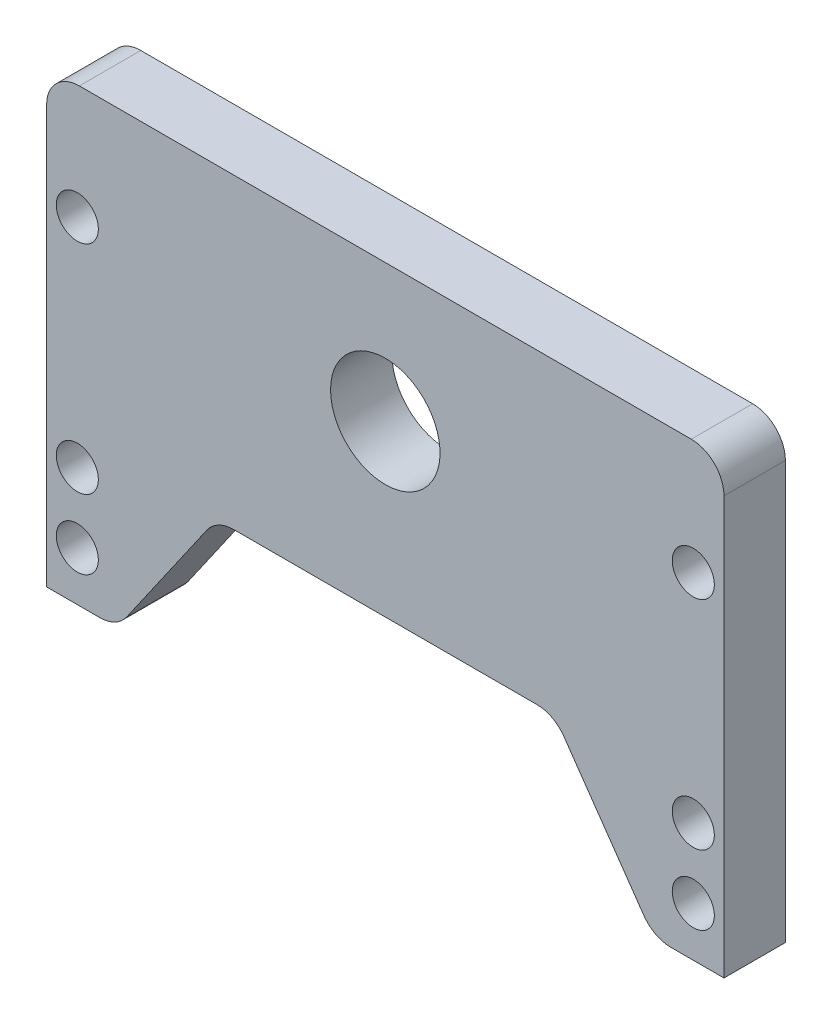
SolidWorks part; units mm, degrees
ref_plane "Front Plane" through (0, 0, 0) normal (0, 0, 1) x (1, 0, 0)
ref_plane "Top Plane" through (0, 0, 0) normal (0, 1, 0) x (1, 0, 0)
ref_plane "Right Plane" through (0, 0, 0) normal (1, 0, 0) x (0, 0, -1)
sketch "Sketch1" plane through (0, 0, 0) normal (0, 0, 1) x (1, 0, 0)
  line L0 (-26.27, -11.1125) -> (-22.1435, -11.1125)
  line L1 (-26.27, -11.1125) -> (-26.27, 21.2725)
  line L2 (-23.7299, 23.8125) -> (23.7299, 23.8125)
  line L3 (26.2699, 21.2725) -> (26.27, -11.1125)
  line L4 (26.27, -11.1125) -> (22.1435, -11.1125)
  line L5 (20.0581, -10.0226) -> (13.8467, -1.0899)
  line L6 (11.7613, 0) -> (-11.7613, 0)
  line L7 (-13.8467, -1.0899) -> (-20.0581, -10.0226)
  line L8 (0, -1000) -> (0, 49000) construction
  line L9 (26.2699, 19.6944) -> (21.5074, 19.6944) construction
  arc A0 (22.1435, -11.1125) -> (20.0581, -10.0226) centre (22.1435, -8.5725) cw
  arc A1 (-22.1435, -11.1125) -> (-20.0581, -10.0226) centre (-22.1435, -8.5725) ccw
  arc A2 (-11.7613, 0) -> (-13.8467, -1.0899) centre (-11.7613, -2.54) ccw
  arc A3 (13.8467, -1.0899) -> (11.7613, 0) centre (11.7613, -2.54) ccw
  arc A4 (-26.27, 21.2725) -> (-23.7299, 23.8125) centre (-23.7299, 21.2725) cw
  arc A5 (23.7299, 23.8125) -> (26.2699, 21.2725) centre (23.7299, 21.2725) cw
  circle A6 centre (23.8887, 14.9319) radius 1.632
  circle A7 centre (23.8887, -7.2931) radius 1.632
  circle A8 centre (-23.8887, -7.2931) radius 1.632
  circle A9 centre (-23.8887, 14.9319) radius 1.632
  circle A10 centre (23.8887, -1.8956) radius 1.632
  circle A11 centre (-23.8887, -1.8956) radius 1.632
  circle A12 centre (0, 13.1413) radius 4.2459
  point P8 (0, 0)
  point P20 (-26.27, 23.8125)
  point P23 (26.2699, 23.8125)
  point P42 (0, 23.8125)
  dimension "D2" = 2.54
  dimension "D5" = 2.54
  dimension "D7" = 3.2639
  dimension "D1" = 52.5399
  dimension "D3" = 11.1125
  dimension "D4" = 34.925
  dimension "D6" = 2.3813
  dimension "D8" = 4.7625
  dimension "D9" = 26.9875
  dimension "D10" = 21.59
extrude "Boss-Extrude1" add sketch "Sketch1" along normal blind 4.7625
